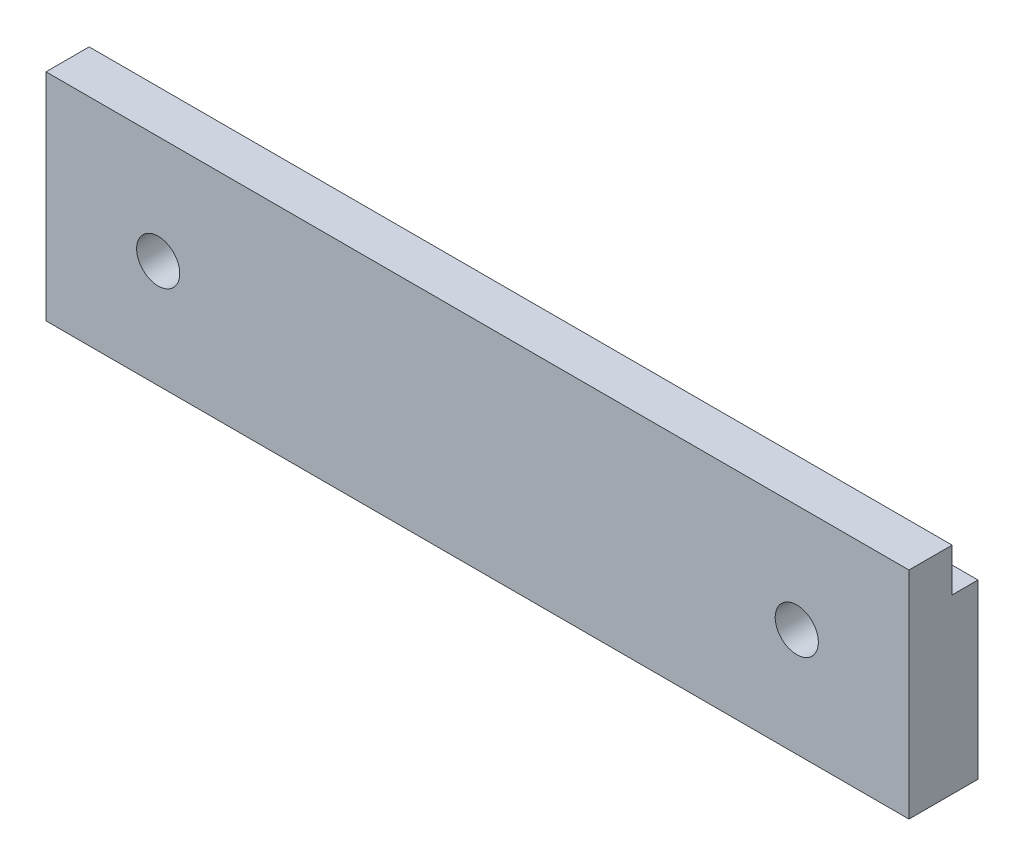
SolidWorks part; units mm, degrees
ref_plane "Front Plane" through (0, 0, 0) normal (0, 0, 1) x (1, 0, 0)
ref_plane "Top Plane" through (0, 0, 0) normal (0, 1, 0) x (1, 0, 0)
ref_plane "Right Plane" through (0, 0, 0) normal (1, 0, 0) x (0, 0, -1)
sketch "Sketch1" plane through (0, 0, 0) normal (1, 0, 0) x (0, 0, -1)
  line L1 (0, 0) -> (8, 0)
  line L2 (0, 0) -> (0, 25)
  line L3 (0, 25) -> (8, 25)
  line L4 (8, 0) -> (8, 25)
  line L5 (8, 25) -> (5, 25)
  line L6 (8, 25) -> (8, 20)
  line L7 (8, 20) -> (5, 20)
  line L8 (5, 25) -> (5, 20)
  line L11 (5, 20) -> (4.8232, 19.8232) construction
  dimension "D1" = 8
  dimension "D2" = 25
  dimension "D3" = 5
  dimension "D4" = 3
  dimension "D7" = 45
extrude "Boss-Extrude1" add sketch "Sketch1" along normal blind 100 contours L8 L3 L2 L1 L4 L7
hole_wizard "Tap Drill for M6x1.0 Tap1" positions "3DSketch1" profile "Sketch4" hole size "M6x1.0" standard "ANSI Metric" end condition through all
sketch3d "3DSketch1"
  line L0 (0, 12.5, 0) -> (100, 12.5, 0) construction
  line L1 (0, 0, 0) -> (0, 25, 0) construction
  line L2 (100, 0, 0) -> (100, 25, 0) construction
  line L4 (50, 25, 0) -> (50, 0, 0) construction
  line L5 (100, 25, 0) -> (0, 25, 0) construction
  line L6 (100, 0, 0) -> (0, 0, 0) construction
  point P0 (87, 12.5, 0)
  point P2 (13, 12.5, 0)
  dimension "D1" = 13
  dimension "D2" = 13
sketch "Sketch4" plane through (87, 12.5, 0) normal (1, 0, 0) x (0, -1, 0)
  line L0 (0, 0) -> (0, 8)
  line L1 (0, 8) -> (2.5, 8)
  line L2 (2.5, 8) -> (2.5, 0)
  line L5 (2.5, 0) -> (0, 0)
  line L11 (0, -6.35) -> (0, 107.95) construction
  dimension "Thru Hole Dia." = 5
  dimension "Thru Hole Depth" = 8
equation "\"depth\"= 8"
equation "\"D1@Sketch1\"=\"depth\""
